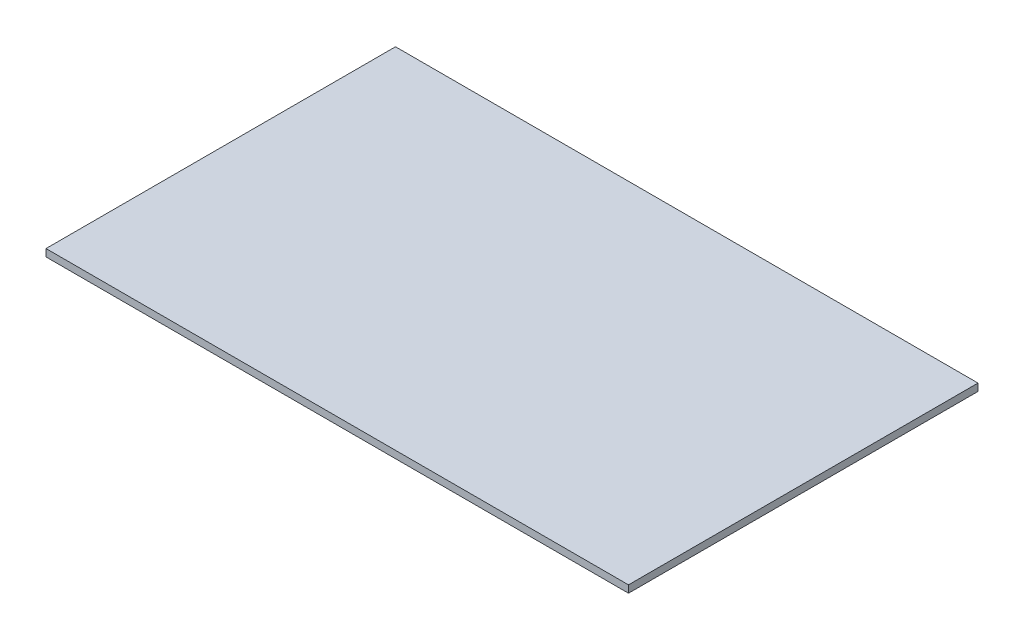
SolidWorks part; units mm, degrees
material "Асботекстолит"
ref_plane "Front Plane" through (0, 0, 0) normal (0, 0, 1) x (1, 0, 0)
ref_plane "Top Plane" through (0, 0, 0) normal (0, 1, 0) x (1, 0, 0)
ref_plane "Right Plane" through (0, 0, 0) normal (1, 0, 0) x (0, 0, -1)
sketch "Sketch1" plane through (0, 0, 0) normal (0, 1, 0) x (1, 0, 0)
  line L1 (-400, 240) -> (400, 240)
  line L2 (-400, 240) -> (-400, -240)
  line L3 (-400, -240) -> (400, -240)
  line L4 (400, 240) -> (400, -240)
  line L5 (-400, 240) -> (400, -240) construction
  line L6 (-400, -240) -> (400, 240) construction
  point P0 (0, 0)
  dimension "D1" = 800
  dimension "D2" = 480
extrude "Boss-Extrude1" add sketch "Sketch1" along normal mid plane 10
sketch "Sketch2" plane through (0, 5, 0) normal (0, 1, 0) x (1, 0, 0)
  line L0 (-250, 222.3104) -> (-250, -210.3127) construction
  line L1 (-485.7026, 0) -> (558.1402, 0) construction
  line L2 (0, 338.4353) -> (0, -308.1146) construction
  line L3 (-400, 240) -> (-400, -240) construction
  line L4 (69.8122, 206.4346) -> (69.8122, -172.729) construction
  dimension "D1" = 150
